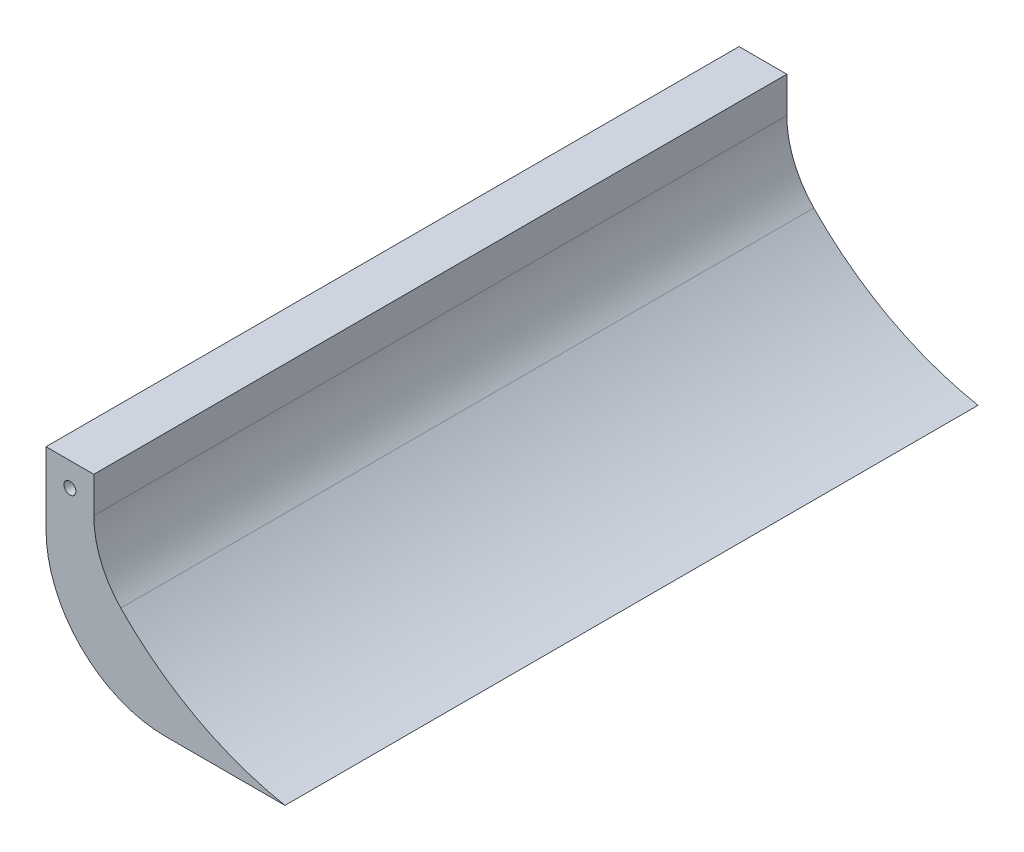
SolidWorks part; units mm, degrees
ref_plane "Front Plane" through (0, 0, 0) normal (0, 0, 1) x (1, 0, 0)
ref_plane "Top Plane" through (0, 0, 0) normal (0, 1, 0) x (1, 0, 0)
ref_plane "Right Plane" through (0, 0, 0) normal (1, 0, 0) x (0, 0, -1)
sketch "Sketch1" plane through (0, 0, 0) normal (0, 0, 1) x (1, 0, 0)
  line L0 (63.5, 0) -> (127, 0)
  line L1 (0, 63.5) -> (0, 101.6)
  line L5 (0, 101.6) -> (25.4, 101.6)
  line L6 (25.4, 101.6) -> (25.4, 82.55)
  arc A0 (39.728, 47.1886) -> (127, 0) centre (158.2621, 162.1132) ccw
  circle A1 centre (12.7, 88.9) radius 3.175
  arc A2 (63.5, 0) -> (0, 63.5) centre (63.5, 63.5) cw
  arc A3 (25.4, 82.55) -> (39.728, 47.1886) centre (76.2, 82.55) ccw
  point P12 (0, 0)
  dimension "D3" = 165.1
  dimension "D4" = 63.5
  dimension "D5" = 50.8
  dimension "D7" = 19.05
  dimension "D8" = 6.35
  dimension "D9" = 12.7
  dimension "D1" = 127
  dimension "D2" = 101.6
  dimension "D6" = 25.4
  dimension "D10" = 12.7
extrude "Boss-Extrude1" add sketch "Sketch1" along normal blind 368.3
